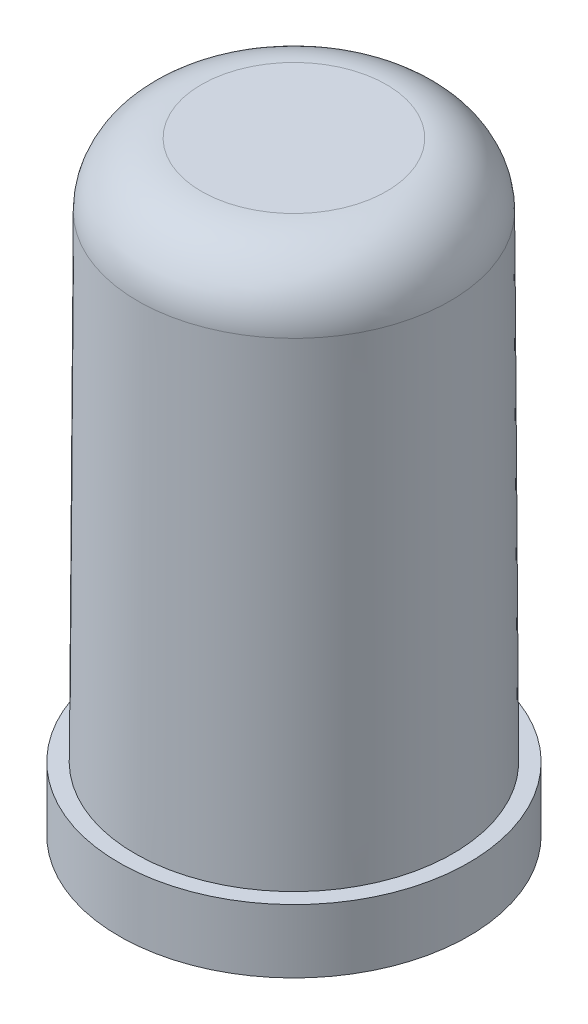
SolidWorks part; units mm, degrees
material "ABS"
ref_plane "前视基准面" through (0, 0, 0) normal (0, 0, 1) x (1, 0, 0)
ref_plane "上视基准面" through (0, 0, 0) normal (0, 1, 0) x (1, 0, 0)
ref_plane "右视基准面" through (0, 0, 0) normal (1, 0, 0) x (0, 0, -1)
sketch "草图1" plane through (0, 0, 0) normal (0, 0, 1) x (1, 0, 0)
  line L0 (0, 19) -> (0, 17)
  line L1 (0, 17) -> (-3.04, 17)
  line L2 (-3.04, 17) -> (-3.04, 0)
  line L3 (-3.04, 0) -> (-5.5, 0)
  line L4 (-5.5, 0) -> (-5.5, 2)
  line L6 (-4.9, 19) -> (0, 19)
  line L7 (-5.5, 2) -> (-5, 2)
  line L8 (-5, 2) -> (-4.9, 19)
  dimension "D1" = 4.9
  dimension "D2" = 5.5
  dimension "D3" = 2
  dimension "D4" = 2
  dimension "D5" = 17
  dimension "D6" = 3.04
  dimension "D7" = 5
revolve "旋转1" add sketch "草图1" angle 360 about L0
fillet "圆角2" radius 2 1 edges at (-3.04, 17, 0)
fillet "圆角3" radius 2 1 edges at (-4.9, 19, 0)
